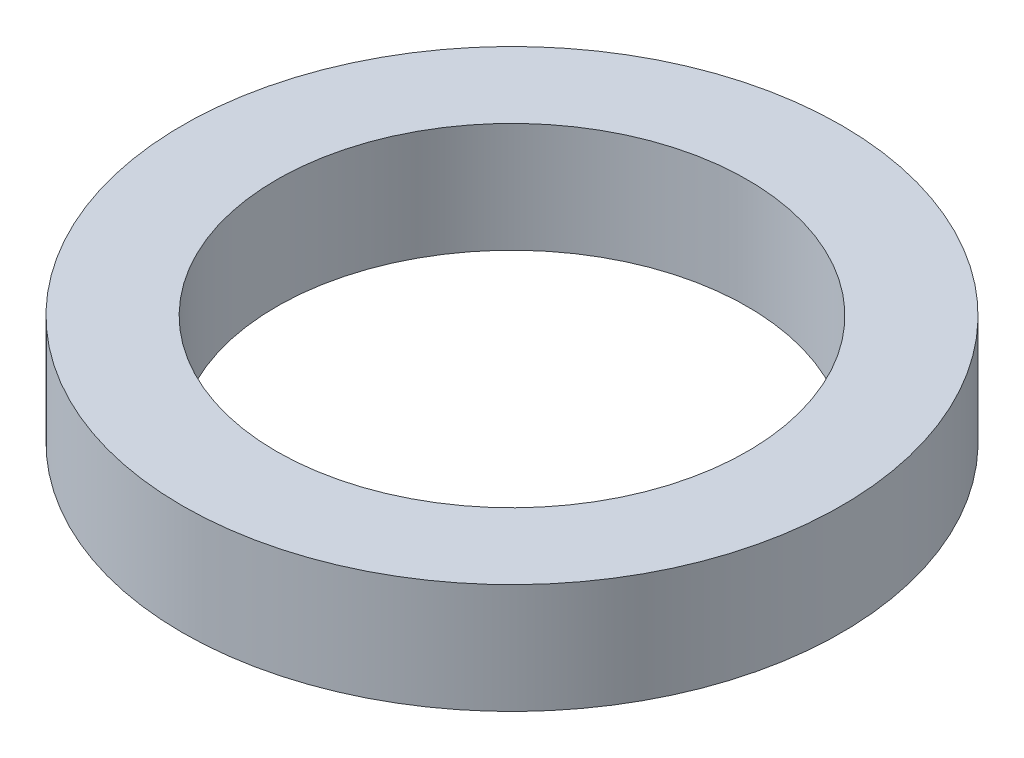
SolidWorks part; units mm, degrees
ref_plane "Front Plane" through (0, 0, 0) normal (0, 0, 1) x (1, 0, 0)
ref_plane "Top Plane" through (0, 0, 0) normal (0, 1, 0) x (1, 0, 0)
ref_plane "Right Plane" through (0, 0, 0) normal (1, 0, 0) x (0, 0, -1)
sketch "Sketch1" plane through (0, 0, 0) normal (0, 1, 0) x (1, 0, 0)
  circle A0 centre (0, 0) radius 533.4
  circle A1 centre (0, 0) radius 381
  dimension "D1" = 762
  dimension "D2" = 1066.8
extrude "Boss-Extrude1" add sketch "Sketch1" along normal blind 177.8
